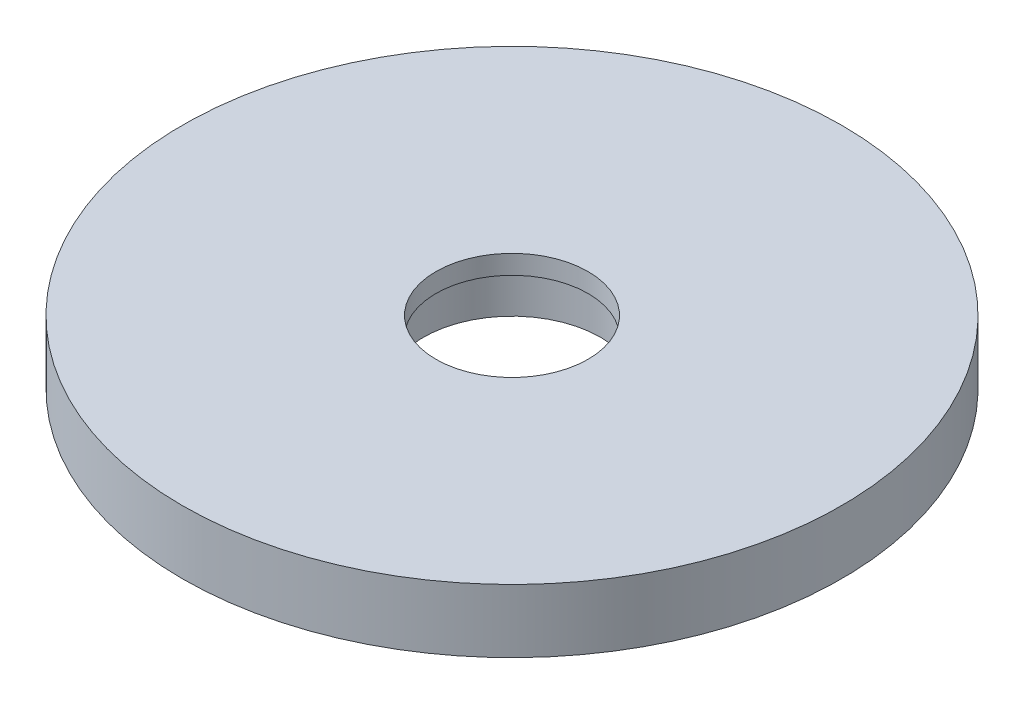
SolidWorks part; units mm, degrees
ref_plane "Front Plane" through (0, 0, 0) normal (0, 0, 1) x (1, 0, 0)
ref_plane "Top Plane" through (0, 0, 0) normal (0, 1, 0) x (1, 0, 0)
ref_plane "Right Plane" through (0, 0, 0) normal (1, 0, 0) x (0, 0, -1)
sketch "Sketch1" plane through (0, 0, 0) normal (0, 1, 0) x (1, 0, 0)
  circle A0 centre (0, 0) radius 52
extrude "Boss-Extrude1" add sketch "Sketch1" along normal blind 10
sketch "Sketch2" plane through (0, 0, 0) normal (0, 1, 0) x (1, 0, 0)
  circle A0 centre (0, 0) radius 50
extrude "Cut-Extrude4" cut sketch "Sketch2" along normal blind 5
sketch "Sketch3" plane through (0, 0, 0) normal (0, 1, 0) x (1, 0, 0)
  circle A0 centre (0, 0) radius 12
extrude "Cut-Extrude7" cut sketch "Sketch3" along normal blind 10
sketch "Sketch4" plane through (0, 5, 0) normal (0, -1, 0) x (1, 0, 0)
  circle A0 centre (0, 0) radius 17
extrude "Boss-Extrude2" add sketch "Sketch4" along normal blind 5
sketch "Sketch5" plane through (0, 0, 0) normal (0, -1, 0) x (1, 0, 0)
  circle A0 centre (0, 0) radius 14
extrude "Cut-Extrude8" cut sketch "Sketch5" against normal blind 7
